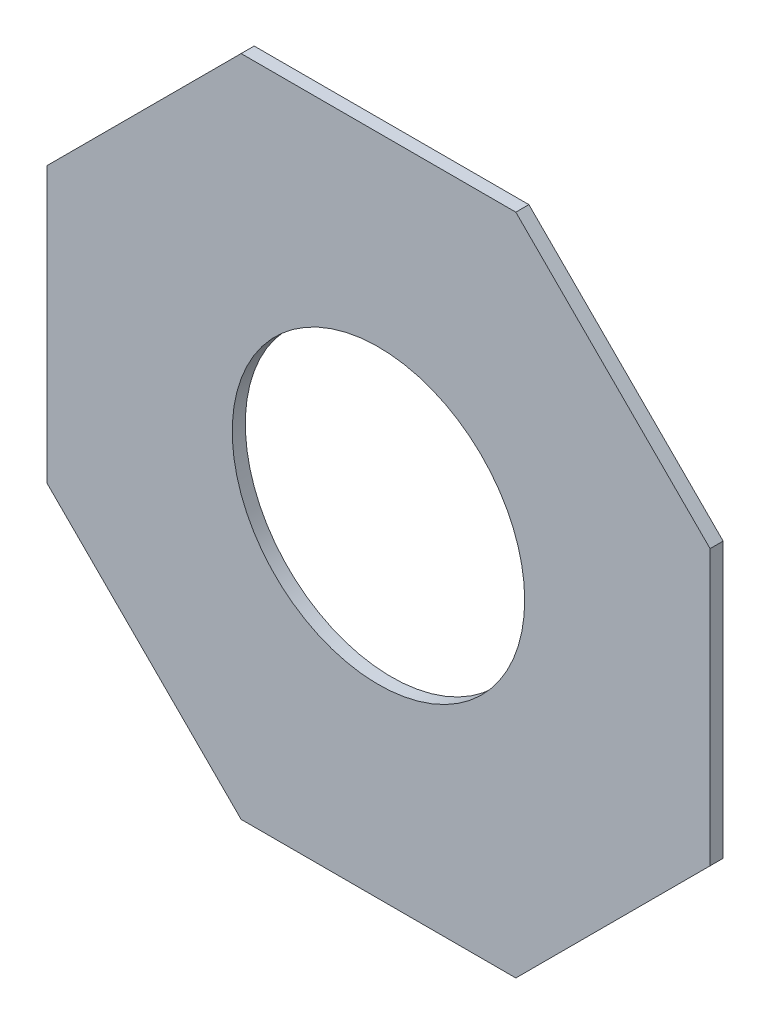
SolidWorks part; units mm, degrees
ref_plane "Ebene vorne" through (0, 0, 0) normal (0, 0, 1) x (1, 0, 0)
ref_plane "Ebene oben" through (0, 0, 0) normal (0, 1, 0) x (1, 0, 0)
ref_plane "Ebene rechts" through (0, 0, 0) normal (1, 0, 0) x (0, 0, -1)
sketch "Skizze1" plane through (0, 0, 0) normal (0, 0, 1) x (1, 0, 0)
  line L1 (1.27, 0.5261) -> (0.5261, 1.27)
  line L2 (0.5261, 1.27) -> (-0.5261, 1.27)
  line L3 (-0.5261, 1.27) -> (-1.27, 0.5261)
  line L4 (-1.27, 0.5261) -> (-1.27, -0.5261)
  line L5 (-1.27, -0.5261) -> (-0.5261, -1.27)
  line L6 (-0.5261, -1.27) -> (0.5261, -1.27)
  line L7 (0.5261, -1.27) -> (1.27, -0.5261)
  line L8 (1.27, -0.5261) -> (1.27, 0.5261)
  circle A0 centre (0, 0) radius 1.27 construction
  circle A1 centre (0, 0) radius 0.56
  dimension "D1" = 2.54
  dimension "D2" = 1.12
extrude "Component_Outline" add sketch "Skizze1" along normal blind 0.05 separate body
sketch3d "3D-Skizze1"
  line L0 (0, 0, 0) -> (1, 0, 0)
  line L1 (0, 0, 0) -> (0, 1, 0)
  line L2 (0, 0, 0) -> (0, 0, 1)
  point P0 (0, 0, 0)
